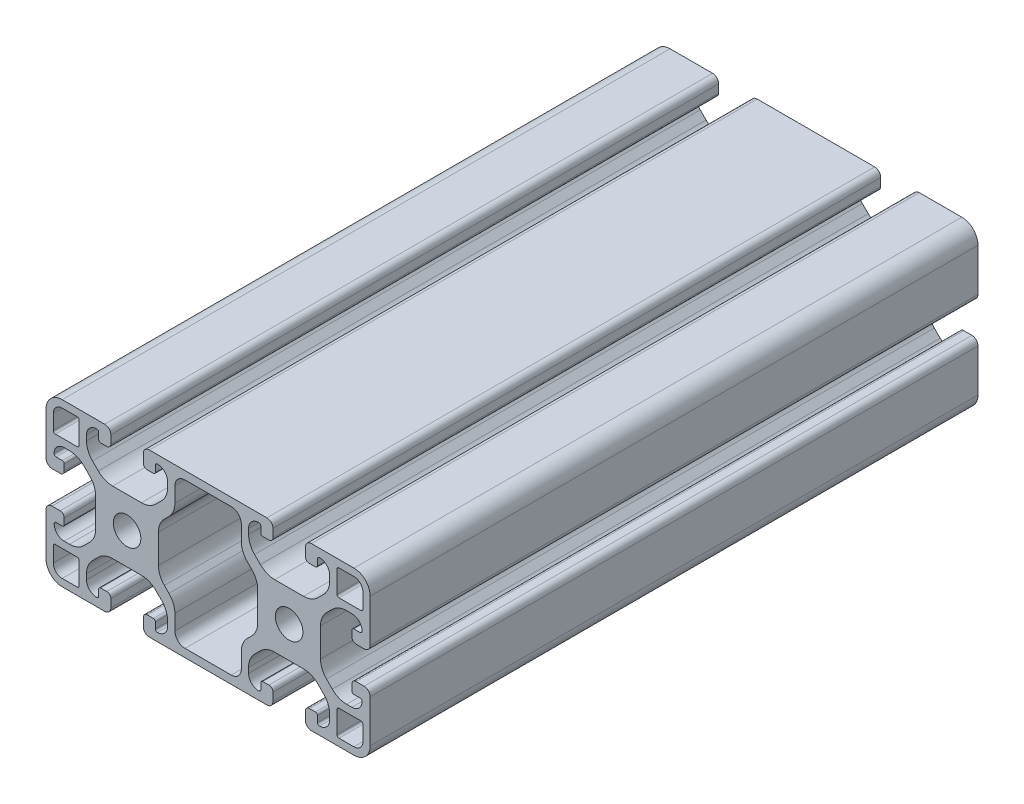
SolidWorks part; units mm, degrees
ref_plane "Plan de face" through (0, 0, 0) normal (0, 0, 1) x (1, 0, 0)
ref_plane "Plan de dessus" through (0, 0, 0) normal (0, 1, 0) x (1, 0, 0)
ref_plane "Plan de droite" through (0, 0, 0) normal (1, 0, 0) x (0, 0, -1)
ref_plane "Plan1" through (0, 0, 20) normal (0, 0, 1) x (1, 0, 0)
sketch "Esquisse1" plane through (0, 0, 20) normal (0, 0, 1) x (1, 0, 0)
  line L0 (66.5, 4.5) -> (65, 4.5)
  line L1 (64, 3.5) -> (64, 1.5)
  line L2 (65.5, 0) -> (76, 0)
  line L3 (80, 4) -> (80, 14.5)
  line L4 (78.5, 16) -> (76.5, 16)
  line L5 (75.5, 15) -> (75.5, 13.5)
  line L6 (76, 13) -> (77.5, 13)
  line L7 (75.5, 10) -> (74.1924, 10)
  line L8 (70.6569, 11.4645) -> (69.2145, 12.9069)
  line L9 (67.75, 16.4424) -> (67.75, 23.5576)
  line L10 (69.2145, 27.0931) -> (70.6569, 28.5355)
  line L11 (74.1924, 30) -> (75.5, 30)
  line L12 (77.5, 27) -> (76, 27)
  line L13 (75.5, 26.5) -> (75.5, 25)
  line L14 (76.5, 24) -> (78.5, 24)
  line L15 (80, 25.5) -> (80, 36)
  line L16 (76, 40) -> (65.5, 40)
  line L17 (64, 38.5) -> (64, 36.5)
  line L18 (65, 35.5) -> (66.5, 35.5)
  line L19 (67, 36) -> (67, 37.5)
  line L20 (70, 35.5) -> (70, 34.1924)
  line L21 (68.5355, 30.6569) -> (67.0931, 29.2145)
  line L22 (63.5576, 27.75) -> (56.4424, 27.75)
  line L23 (52.9069, 29.2145) -> (51.4645, 30.6569)
  line L24 (50, 34.1924) -> (50, 35.5)
  line L25 (53, 37.5) -> (53, 36)
  line L26 (53.5, 35.5) -> (55, 35.5)
  line L27 (56, 36.5) -> (56, 38.5)
  line L28 (54.5, 40) -> (25.5, 40)
  line L29 (24, 38.5) -> (24, 36.5)
  line L30 (25, 35.5) -> (26.5, 35.5)
  line L31 (27, 36) -> (27, 37.5)
  line L32 (30, 35.5) -> (30, 34.1924)
  line L33 (28.5355, 30.6569) -> (27.0931, 29.2145)
  line L34 (23.5576, 27.75) -> (16.4424, 27.75)
  line L35 (12.9069, 29.2145) -> (11.4645, 30.6569)
  line L36 (10, 34.1924) -> (10, 35.5)
  line L37 (13, 37.5) -> (13, 36)
  line L38 (13.5, 35.5) -> (15, 35.5)
  line L39 (16, 36.5) -> (16, 38.5)
  line L40 (14.5, 40) -> (4, 40)
  line L41 (0, 36) -> (0, 25.5)
  line L42 (1.5, 24) -> (3.5, 24)
  line L43 (4.5, 25) -> (4.5, 26.5)
  line L44 (4, 27) -> (2.5, 27)
  line L45 (4.5, 30) -> (5.8076, 30)
  line L46 (9.3431, 28.5355) -> (10.7855, 27.0931)
  line L47 (12.25, 23.5576) -> (12.25, 16.4424)
  line L48 (10.7855, 12.9069) -> (9.3431, 11.4645)
  line L49 (5.8076, 10) -> (4.5, 10)
  line L50 (2.5, 13) -> (4, 13)
  line L51 (4.5, 13.5) -> (4.5, 15)
  line L52 (3.5, 16) -> (1.5, 16)
  line L53 (0, 14.5) -> (0, 4)
  line L54 (4, 0) -> (14.5, 0)
  line L55 (16, 1.5) -> (16, 3.5)
  line L56 (15, 4.5) -> (13.5, 4.5)
  line L57 (13, 4) -> (13, 2.5)
  line L58 (10, 4.5) -> (10, 5.8076)
  line L59 (11.4645, 9.3431) -> (12.9069, 10.7855)
  line L60 (16.4424, 12.25) -> (23.5576, 12.25)
  line L61 (27.0931, 10.7855) -> (28.5355, 9.3431)
  line L62 (30, 5.8076) -> (30, 4.5)
  line L63 (27, 2.5) -> (27, 4)
  line L64 (26.5, 4.5) -> (25, 4.5)
  line L65 (24, 3.5) -> (24, 1.5)
  line L66 (25.5, 0) -> (54.5, 0)
  line L67 (56, 1.5) -> (56, 3.5)
  line L68 (55, 4.5) -> (53.5, 4.5)
  line L69 (53, 4) -> (53, 2.5)
  line L70 (50, 4.5) -> (50, 5.8076)
  line L71 (51.4645, 9.3431) -> (52.9069, 10.7855)
  line L72 (56.4424, 12.25) -> (63.5576, 12.25)
  line L73 (67.0931, 10.7855) -> (68.5355, 9.3431)
  line L74 (70, 5.8076) -> (70, 4.5)
  line L75 (67, 2.5) -> (67, 4)
  line L76 (31.8, 4.5) -> (31.8, 8.2503)
  line L77 (30.3355, 11.7858) -> (29.2145, 12.9069)
  line L78 (27.75, 16.4424) -> (27.75, 23.5576)
  line L79 (29.2145, 27.0931) -> (30.3355, 28.2142)
  line L80 (31.8, 31.7497) -> (31.8, 35.5)
  line L81 (34.3, 38) -> (45.7, 38)
  line L82 (48.2, 35.5) -> (48.2, 31.7497)
  line L83 (49.6645, 28.2142) -> (50.7855, 27.0931)
  line L84 (52.25, 23.5576) -> (52.25, 16.4424)
  line L85 (50.7855, 12.9069) -> (49.6645, 11.7858)
  line L86 (48.2, 8.2503) -> (48.2, 4.5)
  line L87 (45.7, 2) -> (34.3, 2)
  line L88 (7.7, 1.8) -> (4, 1.8)
  line L89 (1.8, 4) -> (1.8, 7.7)
  line L90 (2.3, 8.2) -> (7.7, 8.2)
  line L91 (8.2, 7.7) -> (8.2, 2.3)
  line L92 (72.3, 38.2) -> (76, 38.2)
  line L93 (78.2, 36) -> (78.2, 32.3)
  line L94 (77.7, 31.8) -> (72.3, 31.8)
  line L95 (71.8, 32.3) -> (71.8, 37.7)
  line L96 (78.2, 7.7) -> (78.2, 4)
  line L97 (76, 1.8) -> (72.3, 1.8)
  line L98 (71.8, 2.3) -> (71.8, 7.7)
  line L99 (72.3, 8.2) -> (77.7, 8.2)
  line L100 (1.8, 32.3) -> (1.8, 36)
  line L101 (4, 38.2) -> (7.7, 38.2)
  line L102 (8.2, 37.7) -> (8.2, 32.3)
  line L103 (7.7, 31.8) -> (2.3, 31.8)
  arc A0 (67, 4) -> (66.5, 4.5) centre (66.5, 4) ccw
  arc A1 (65, 4.5) -> (64, 3.5) centre (65, 3.5) ccw
  arc A2 (64, 1.5) -> (65.5, 0) centre (65.5, 1.5) ccw
  arc A3 (76, 0) -> (80, 4) centre (76, 4) ccw
  arc A4 (80, 14.5) -> (78.5, 16) centre (78.5, 14.5) ccw
  arc A5 (76.5, 16) -> (75.5, 15) centre (76.5, 15) ccw
  arc A6 (75.5, 13.5) -> (76, 13) centre (76, 13.5) ccw
  arc A7 (77.5, 13) -> (78, 12.5) centre (77.5, 12.5) cw
  arc A8 (78, 12.5) -> (75.5, 10) centre (75.5, 12.5) cw
  arc A9 (74.1924, 10) -> (70.6569, 11.4645) centre (74.1924, 15) cw
  arc A10 (69.2145, 12.9069) -> (67.75, 16.4424) centre (72.75, 16.4424) cw
  arc A11 (67.75, 23.5576) -> (69.2145, 27.0931) centre (72.75, 23.5576) cw
  arc A12 (70.6569, 28.5355) -> (74.1924, 30) centre (74.1924, 25) cw
  arc A13 (75.5, 30) -> (78, 27.5) centre (75.5, 27.5) cw
  arc A14 (78, 27.5) -> (77.5, 27) centre (77.5, 27.5) cw
  arc A15 (76, 27) -> (75.5, 26.5) centre (76, 26.5) ccw
  arc A16 (75.5, 25) -> (76.5, 24) centre (76.5, 25) ccw
  arc A17 (78.5, 24) -> (80, 25.5) centre (78.5, 25.5) ccw
  arc A18 (80, 36) -> (76, 40) centre (76, 36) ccw
  arc A19 (65.5, 40) -> (64, 38.5) centre (65.5, 38.5) ccw
  arc A20 (64, 36.5) -> (65, 35.5) centre (65, 36.5) ccw
  arc A21 (66.5, 35.5) -> (67, 36) centre (66.5, 36) ccw
  arc A22 (67, 37.5) -> (67.5, 38) centre (67.5, 37.5) cw
  arc A23 (67.5, 38) -> (70, 35.5) centre (67.5, 35.5) cw
  arc A24 (70, 34.1924) -> (68.5355, 30.6569) centre (65, 34.1924) cw
  arc A25 (67.0931, 29.2145) -> (63.5576, 27.75) centre (63.5576, 32.75) cw
  arc A26 (56.4424, 27.75) -> (52.9069, 29.2145) centre (56.4424, 32.75) cw
  arc A27 (51.4645, 30.6569) -> (50, 34.1924) centre (55, 34.1924) cw
  arc A28 (50, 35.5) -> (52.5, 38) centre (52.5, 35.5) cw
  arc A29 (52.5, 38) -> (53, 37.5) centre (52.5, 37.5) cw
  arc A30 (53, 36) -> (53.5, 35.5) centre (53.5, 36) ccw
  arc A31 (55, 35.5) -> (56, 36.5) centre (55, 36.5) ccw
  arc A32 (56, 38.5) -> (54.5, 40) centre (54.5, 38.5) ccw
  arc A33 (25.5, 40) -> (24, 38.5) centre (25.5, 38.5) ccw
  arc A34 (24, 36.5) -> (25, 35.5) centre (25, 36.5) ccw
  arc A35 (26.5, 35.5) -> (27, 36) centre (26.5, 36) ccw
  arc A36 (27, 37.5) -> (27.5, 38) centre (27.5, 37.5) cw
  arc A37 (27.5, 38) -> (30, 35.5) centre (27.5, 35.5) cw
  arc A38 (30, 34.1924) -> (28.5355, 30.6569) centre (25, 34.1924) cw
  arc A39 (27.0931, 29.2145) -> (23.5576, 27.75) centre (23.5576, 32.75) cw
  arc A40 (16.4424, 27.75) -> (12.9069, 29.2145) centre (16.4424, 32.75) cw
  arc A41 (11.4645, 30.6569) -> (10, 34.1924) centre (15, 34.1924) cw
  arc A42 (10, 35.5) -> (12.5, 38) centre (12.5, 35.5) cw
  arc A43 (12.5, 38) -> (13, 37.5) centre (12.5, 37.5) cw
  arc A44 (13, 36) -> (13.5, 35.5) centre (13.5, 36) ccw
  arc A45 (15, 35.5) -> (16, 36.5) centre (15, 36.5) ccw
  arc A46 (16, 38.5) -> (14.5, 40) centre (14.5, 38.5) ccw
  arc A47 (4, 40) -> (0, 36) centre (4, 36) ccw
  arc A48 (0, 25.5) -> (1.5, 24) centre (1.5, 25.5) ccw
  arc A49 (3.5, 24) -> (4.5, 25) centre (3.5, 25) ccw
  arc A50 (4.5, 26.5) -> (4, 27) centre (4, 26.5) ccw
  arc A51 (2.5, 27) -> (2, 27.5) centre (2.5, 27.5) cw
  arc A52 (2, 27.5) -> (4.5, 30) centre (4.5, 27.5) cw
  arc A53 (5.8076, 30) -> (9.3431, 28.5355) centre (5.8076, 25) cw
  arc A54 (10.7855, 27.0931) -> (12.25, 23.5576) centre (7.25, 23.5576) cw
  arc A55 (12.25, 16.4424) -> (10.7855, 12.9069) centre (7.25, 16.4424) cw
  arc A56 (9.3431, 11.4645) -> (5.8076, 10) centre (5.8076, 15) cw
  arc A57 (4.5, 10) -> (2, 12.5) centre (4.5, 12.5) cw
  arc A58 (2, 12.5) -> (2.5, 13) centre (2.5, 12.5) cw
  arc A59 (4, 13) -> (4.5, 13.5) centre (4, 13.5) ccw
  arc A60 (4.5, 15) -> (3.5, 16) centre (3.5, 15) ccw
  arc A61 (1.5, 16) -> (0, 14.5) centre (1.5, 14.5) ccw
  arc A62 (0, 4) -> (4, 0) centre (4, 4) ccw
  arc A63 (14.5, 0) -> (16, 1.5) centre (14.5, 1.5) ccw
  arc A64 (16, 3.5) -> (15, 4.5) centre (15, 3.5) ccw
  arc A65 (13.5, 4.5) -> (13, 4) centre (13.5, 4) ccw
  arc A66 (13, 2.5) -> (12.5, 2) centre (12.5, 2.5) cw
  arc A67 (12.5, 2) -> (10, 4.5) centre (12.5, 4.5) cw
  arc A68 (10, 5.8076) -> (11.4645, 9.3431) centre (15, 5.8076) cw
  arc A69 (12.9069, 10.7855) -> (16.4424, 12.25) centre (16.4424, 7.25) cw
  arc A70 (23.5576, 12.25) -> (27.0931, 10.7855) centre (23.5576, 7.25) cw
  arc A71 (28.5355, 9.3431) -> (30, 5.8076) centre (25, 5.8076) cw
  arc A72 (30, 4.5) -> (27.5, 2) centre (27.5, 4.5) cw
  arc A73 (27.5, 2) -> (27, 2.5) centre (27.5, 2.5) cw
  arc A74 (27, 4) -> (26.5, 4.5) centre (26.5, 4) ccw
  arc A75 (25, 4.5) -> (24, 3.5) centre (25, 3.5) ccw
  arc A76 (24, 1.5) -> (25.5, 0) centre (25.5, 1.5) ccw
  arc A77 (54.5, 0) -> (56, 1.5) centre (54.5, 1.5) ccw
  arc A78 (56, 3.5) -> (55, 4.5) centre (55, 3.5) ccw
  arc A79 (53.5, 4.5) -> (53, 4) centre (53.5, 4) ccw
  arc A80 (53, 2.5) -> (52.5, 2) centre (52.5, 2.5) cw
  arc A81 (52.5, 2) -> (50, 4.5) centre (52.5, 4.5) cw
  arc A82 (50, 5.8076) -> (51.4645, 9.3431) centre (55, 5.8076) cw
  arc A83 (52.9069, 10.7855) -> (56.4424, 12.25) centre (56.4424, 7.25) cw
  arc A84 (63.5576, 12.25) -> (67.0931, 10.7855) centre (63.5576, 7.25) cw
  arc A85 (68.5355, 9.3431) -> (70, 5.8076) centre (65, 5.8076) cw
  arc A86 (70, 4.5) -> (67.5, 2) centre (67.5, 4.5) cw
  arc A87 (67.5, 2) -> (67, 2.5) centre (67.5, 2.5) cw
  circle A88 centre (20, 20) radius 3.4
  circle A89 centre (60, 20) radius 3.4
  arc A90 (34.3, 2) -> (31.8, 4.5) centre (34.3, 4.5) cw
  arc A91 (31.8, 8.2503) -> (30.3355, 11.7858) centre (26.8, 8.2503) ccw
  arc A92 (29.2145, 12.9069) -> (27.75, 16.4424) centre (32.75, 16.4424) cw
  arc A93 (27.75, 23.5576) -> (29.2145, 27.0931) centre (32.75, 23.5576) cw
  arc A94 (30.3355, 28.2142) -> (31.8, 31.7497) centre (26.8, 31.7497) ccw
  arc A95 (31.8, 35.5) -> (34.3, 38) centre (34.3, 35.5) cw
  arc A96 (45.7, 38) -> (48.2, 35.5) centre (45.7, 35.5) cw
  arc A97 (48.2, 31.7497) -> (49.6645, 28.2142) centre (53.2, 31.7497) ccw
  arc A98 (50.7855, 27.0931) -> (52.25, 23.5576) centre (47.25, 23.5576) cw
  arc A99 (52.25, 16.4424) -> (50.7855, 12.9069) centre (47.25, 16.4424) cw
  arc A100 (49.6645, 11.7858) -> (48.2, 8.2503) centre (53.2, 8.2503) ccw
  arc A101 (48.2, 4.5) -> (45.7, 2) centre (45.7, 4.5) cw
  arc A102 (8.2, 2.3) -> (7.7, 1.8) centre (7.7, 2.3) cw
  arc A103 (4, 1.8) -> (1.8, 4) centre (4, 4) cw
  arc A104 (1.8, 7.7) -> (2.3, 8.2) centre (2.3, 7.7) cw
  arc A105 (7.7, 8.2) -> (8.2, 7.7) centre (7.7, 7.7) cw
  arc A106 (71.8, 37.7) -> (72.3, 38.2) centre (72.3, 37.7) cw
  arc A107 (76, 38.2) -> (78.2, 36) centre (76, 36) cw
  arc A108 (78.2, 32.3) -> (77.7, 31.8) centre (77.7, 32.3) cw
  arc A109 (72.3, 31.8) -> (71.8, 32.3) centre (72.3, 32.3) cw
  arc A110 (77.7, 8.2) -> (78.2, 7.7) centre (77.7, 7.7) cw
  arc A111 (78.2, 4) -> (76, 1.8) centre (76, 4) cw
  arc A112 (72.3, 1.8) -> (71.8, 2.3) centre (72.3, 2.3) cw
  arc A113 (71.8, 7.7) -> (72.3, 8.2) centre (72.3, 7.7) cw
  arc A114 (2.3, 31.8) -> (1.8, 32.3) centre (2.3, 32.3) cw
  arc A115 (1.8, 36) -> (4, 38.2) centre (4, 36) cw
  arc A116 (7.7, 38.2) -> (8.2, 37.7) centre (7.7, 37.7) cw
  arc A117 (8.2, 32.3) -> (7.7, 31.8) centre (7.7, 32.3) cw
extrude "Boss.-Extru.1" add sketch "Esquisse1" against normal blind 150
